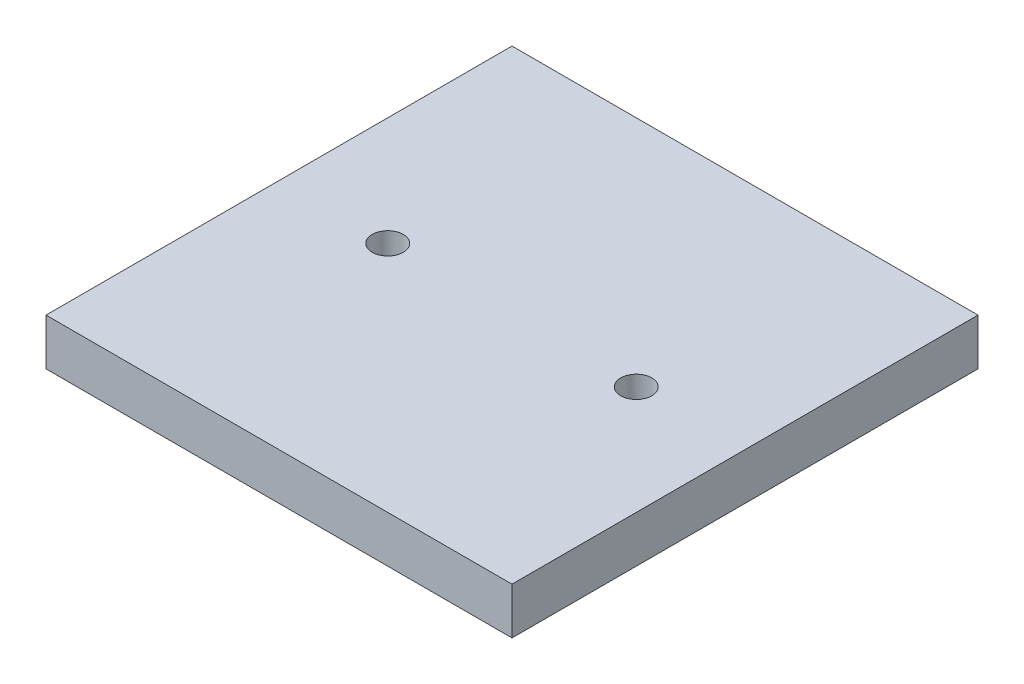
SolidWorks part; units mm, degrees
ref_plane "Front Plane" through (0, 0, 0) normal (0, 0, 1) x (1, 0, 0)
ref_plane "Top Plane" through (0, 0, 0) normal (0, 1, 0) x (1, 0, 0)
ref_plane "Right Plane" through (0, 0, 0) normal (1, 0, 0) x (0, 0, -1)
sketch "Sketch1" plane through (0, 0, 0) normal (0, 1, 0) x (1, 0, 0)
  line L1 (-15, 15) -> (15, 15)
  line L2 (-15, 15) -> (-15, -15)
  line L3 (-15, -15) -> (15, -15)
  line L4 (15, 15) -> (15, -15)
  line L5 (-15, 15) -> (15, -15) construction
  line L6 (-15, -15) -> (15, 15) construction
  point P0 (0, 0)
  dimension "D1" = 30
  dimension "D2" = 30
extrude "Boss-Extrude1" add sketch "Sketch1" along normal blind 3
sketch "Sketch2" plane through (0, 3, 0) normal (0, 1, 0) x (1, 0, 0)
  line L0 (-8, 0) -> (8, 0) construction
  circle A0 centre (-8, 0) radius 1
  circle A1 centre (8, 0) radius 1
  point P5 (0, 0)
  dimension "D1" = 2
  dimension "D2" = 2
  dimension "D3" = 16
extrude "Cut-Extrude1" cut sketch "Sketch2" against normal blind 3
